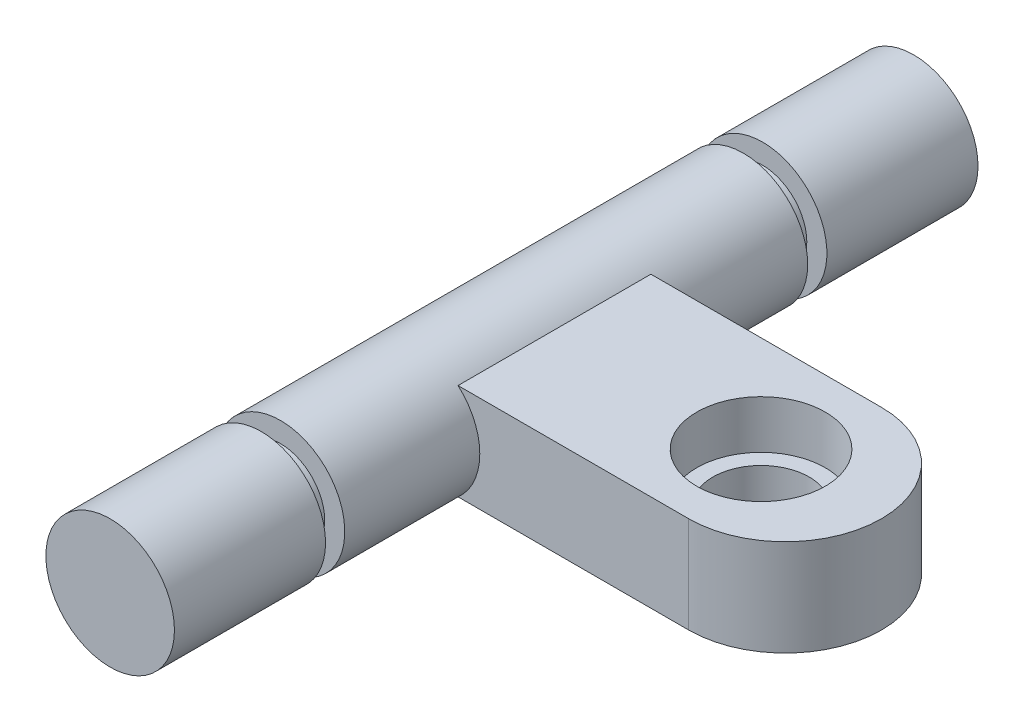
SolidWorks part; units mm, degrees
material "Plain Carbon Steel"
ref_plane "Front Plane" through (0, 0, 0) normal (0, 0, 1) x (1, 0, 0)
ref_plane "Top Plane" through (0, 0, 0) normal (0, 1, 0) x (1, 0, 0)
ref_plane "Right Plane" through (0, 0, 0) normal (1, 0, 0) x (0, 0, -1)
sketch "Sketch3" plane through (0, 0, 0) normal (0, 1, 0) x (1, 0, 0)
  line L1 (8.5, -6) -> (-8.5, -6)
  line L3 (8.5, 6) -> (-8.5, 6)
  line L4 (-8.5, -6) -> (-8.5, 6)
  line L5 (0, 6) -> (0, -6) construction
  line L6 (7, 0) -> (-8.5, 0) construction
  arc A0 (8.5, 6) -> (8.5, -6) centre (8.5, 0) cw
  circle A1 centre (7, 0) radius 3
  point P0 (0, 0)
  dimension "D3" = 6
  dimension "D1" = 12
  dimension "D2" = 17
  dimension "D4" = 7
sketch3d "3DSketch2"
  line L0 (-8.5, 0, 6) -> (-8.5, 0, -6) construction
  line L1 (7, 0, 0) -> (-8.5, 0, 0) construction
extrude "Boss-Extrude1" add sketch "Sketch3" along normal mid plane 6
sketch "Sketch4" plane through (0, 3, 0) normal (0, 1, 0) x (1, 0, 0)
  circle A0 centre (7, 0) radius 4
  dimension "D1" = 8
extrude "Cut-Extrude1" cut sketch "Sketch4" against normal blind 3
sketch "Sketch6" plane through (0, 0, 0) normal (0, 0, 1) x (1, 0, 0)
  line L0 (-8.5, 3) -> (-8.5, -3) construction
  circle A0 centre (-8.5, 0) radius 4
  dimension "D1" = 8
extrude "Boss-Extrude2" add sketch "Sketch6" along normal mid plane 50
sketch "Sketch7" plane through (0, 0, 0) normal (0, 1, 0) x (1, 0, 0)
  line L3 (-4.5, 6) -> (-4.5, 25) construction
  line L8 (-3.25, 14.4024) -> (-5.75, 14.4024)
  line L9 (-3.25, 14.4024) -> (-3.25, 15.5976)
  line L10 (-3.25, 15.5976) -> (-5.75, 15.5976)
  line L11 (-5.75, 14.4024) -> (-5.75, 15.5976)
  line L12 (-4.5, 15.5976) -> (-4.5, 14.4024) construction
  line L13 (-3.25, 15) -> (-5.75, 15) construction
  line L14 (-37.5, 0) -> (37.5, 0) construction
  line L15 (-4.4, 0) -> (4.4, 0) construction
  line L16 (-3.25, -15) -> (-5.75, -15) construction
  line L17 (-4.5, -15.5976) -> (-4.5, -14.4024) construction
  line L18 (-5.75, -14.4024) -> (-5.75, -15.5976)
  line L19 (-3.25, -15.5976) -> (-5.75, -15.5976)
  line L20 (-3.25, -14.4024) -> (-3.25, -15.5976)
  line L21 (-3.25, -14.4024) -> (-5.75, -14.4024)
  point P0 (-4.5, 15)
  point P18 (-4.5, -15)
  dimension "D1" = 15
  dimension "D2" = 2.5
sketch "Sketch8" plane through (0, 0, 25) normal (0, 0, 1) x (1, 0, 0)
  point P0 (-8.5, 0)
sketch3d "3DSketch3"
  line L0 (-8.5, 0, 25) -> (-8.5, 0, -24.3982) construction
revolve "Cut-Revolve1" cut sketch "Sketch7" angle 360 about L0
